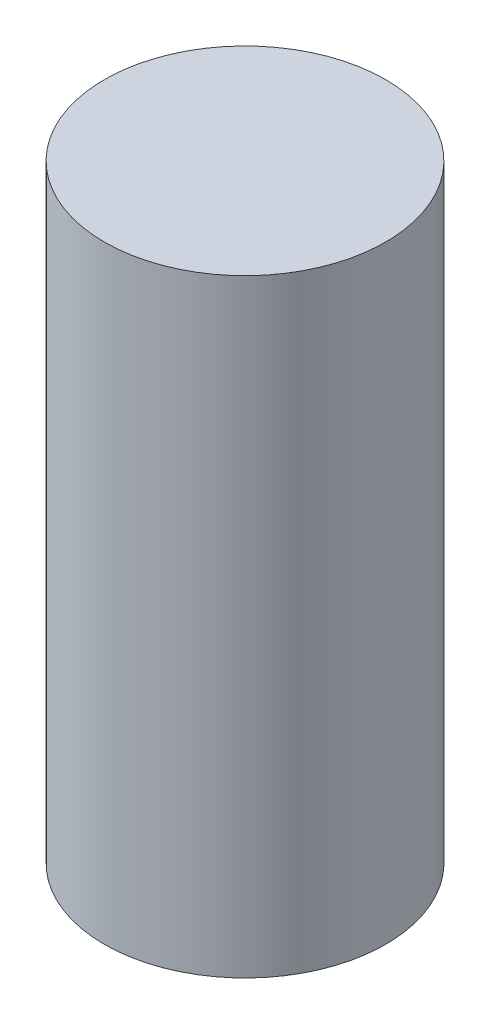
SolidWorks part; units mm, degrees
ref_plane "Front Plane" through (0, 0, 0) normal (0, 0, 1) x (1, 0, 0)
ref_plane "Top Plane" through (0, 0, 0) normal (0, 1, 0) x (1, 0, 0)
ref_plane "Right Plane" through (0, 0, 0) normal (1, 0, 0) x (0, 0, -1)
sketch "Sketch1" plane through (0, 0, 0) normal (0, 1, 0) x (1, 0, 0)
  circle A0 centre (0, 0) radius 6.8
  dimension "D1" = 13.6
extrude "Boss-Extrude1" add sketch "Sketch1" along normal blind 29.4
